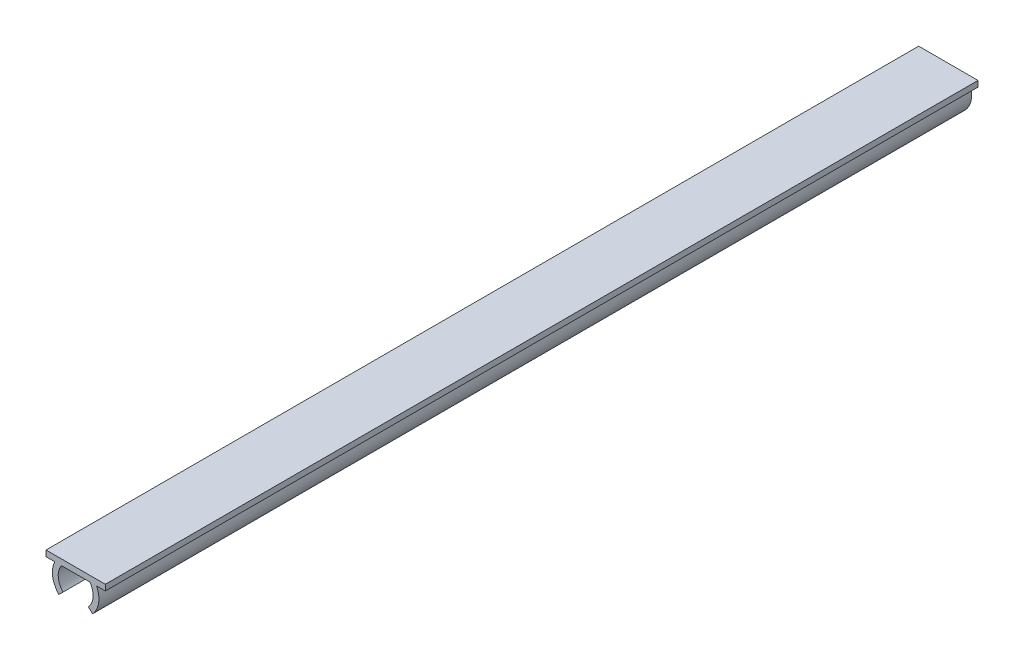
SolidWorks part; units mm, degrees
ref_plane "前视基准面" through (0, 0, 0) normal (0, 0, 1) x (1, 0, 0)
ref_plane "上视基准面" through (0, 0, 0) normal (0, 1, 0) x (1, 0, 0)
ref_plane "右视基准面" through (0, 0, 0) normal (1, 0, 0) x (0, 0, -1)
sketch "草图1" plane through (0, 0, 0) normal (0, 0, 1) x (1, 0, 0)
  line L0 (-5.5286, 2.4615) -> (4.6714, 2.4615)
  line L1 (-5.5286, 1.4615) -> (-4.0254, 1.4615)
  line L2 (-2.8653, 1.4615) -> (2.0081, 1.4615)
  line L3 (3.1683, 1.4615) -> (4.6714, 1.4615)
  line L4 (-3.3333, -3.0385) -> (-2.6071, -2.351)
  line L5 (1.75, -2.351) -> (2.4762, -3.0385)
  line L6 (-5.5286, 2.4615) -> (-5.5286, 1.4615)
  line L7 (4.6714, 2.4615) -> (4.6714, 1.4615)
  arc A0 (-4.0254, 1.4615) -> (-3.3333, -3.0385) centre (-0.4286, -0.2885) ccw
  arc A1 (-2.8653, 1.4615) -> (-2.6071, -2.351) centre (-0.4286, -0.2885) ccw
  arc A2 (2.4762, -3.0385) -> (3.1683, 1.4615) centre (-0.4286, -0.2885) ccw
  arc A3 (1.75, -2.351) -> (2.0081, 1.4615) centre (-0.4286, -0.2885) ccw
extrude "凸台-拉伸1" add sketch "草图1" along normal blind 150
